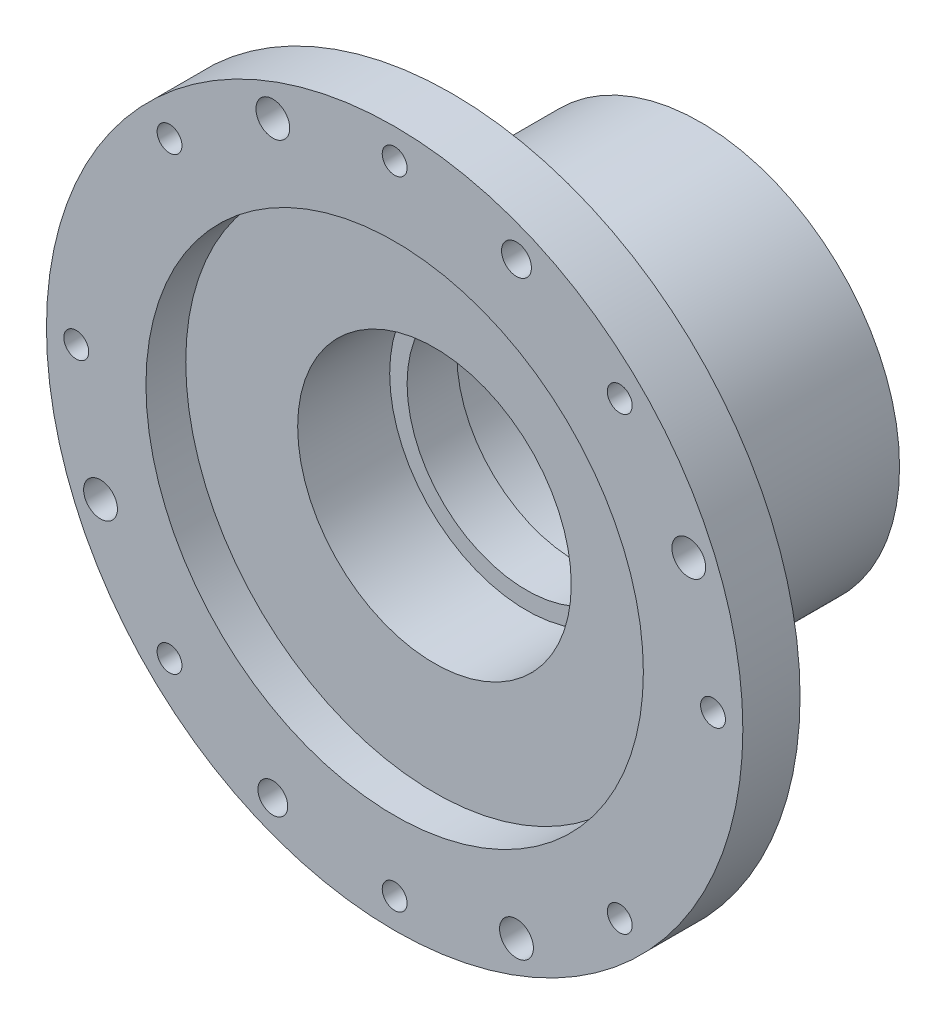
SolidWorks part; units mm, degrees
material "0.7050 (EN-GJS-500-7)"
ref_plane "Front Plane" through (0, 0, 0) normal (0, 0, 1) x (1, 0, 0)
ref_plane "Top Plane" through (0, 0, 0) normal (0, 1, 0) x (1, 0, 0)
ref_plane "Right Plane" through (0, 0, 0) normal (1, 0, 0) x (0, 0, -1)
sketch "Sketch1" plane through (0, 0, 0) normal (0, 1, 0) x (1, 0, 0)
  line L0 (27.5, 96) -> (40, 96)
  line L1 (40, 96) -> (40, 46)
  line L2 (40, 46) -> (70, 46)
  line L3 (70, 46) -> (70, 34.5)
  line L4 (70, 34.5) -> (50, 34.5)
  line L5 (50, 34.5) -> (50, 42.5)
  line L6 (50, 42.5) -> (27.5, 42.5)
  line L7 (27.5, 42.5) -> (27.5, 61)
  line L8 (27.5, 61) -> (24, 61)
  line L9 (24, 61) -> (24, 71)
  line L10 (24, 71) -> (27.5, 71)
  line L11 (27.5, 71) -> (27.5, 96)
  line L12 (0, -150) -> (0, 150) construction
revolve "REV_Output_Housing_Body" add sketch "Sketch1" angle 360 about L12
sketch "Sketch2" plane through (0, 0, 0) normal (0, 0, 1) x (1, 0, 0)
  circle A0 centre (64, 0) radius 2.5
  circle A1 centre (45.2548, 45.2548) radius 2.5
  circle A2 centre (0, 64) radius 2.5
  circle A3 centre (-45.2548, 45.2548) radius 2.5
  circle A4 centre (-64, 0) radius 2.5
  circle A5 centre (-45.2548, -45.2548) radius 2.5
  circle A6 centre (0, -64) radius 2.5
  circle A7 centre (45.2548, -45.2548) radius 2.5
  circle A8 centre (24.4917, 59.1283) radius 3
  circle A9 centre (-24.4917, -59.1283) radius 3
  circle A10 centre (59.1283, 24.4917) radius 3.4
  circle A11 centre (-24.4917, 59.1283) radius 3.4
  circle A12 centre (-59.1283, -24.4917) radius 3.4
  circle A13 centre (24.4917, -59.1283) radius 3.4
extrude "CUT_8xM6_Tie_2xDowel_4xM8_Mount_PCD128" cut sketch "Sketch2" along normal mid plane 300
sketch "Sketch3" plane through (0, 0, -96) normal (0, 0, -1) x (-1, 0, 0)
  circle A0 centre (23.8649, 23.8649) radius 1.65
  circle A1 centre (-23.8649, 23.8649) radius 1.65
  circle A2 centre (-23.8649, -23.8649) radius 1.65
  circle A3 centre (23.8649, -23.8649) radius 1.65
extrude "CUT_4xM4_Seal_Cover_Taps" cut sketch "Sketch3" against normal blind 10
